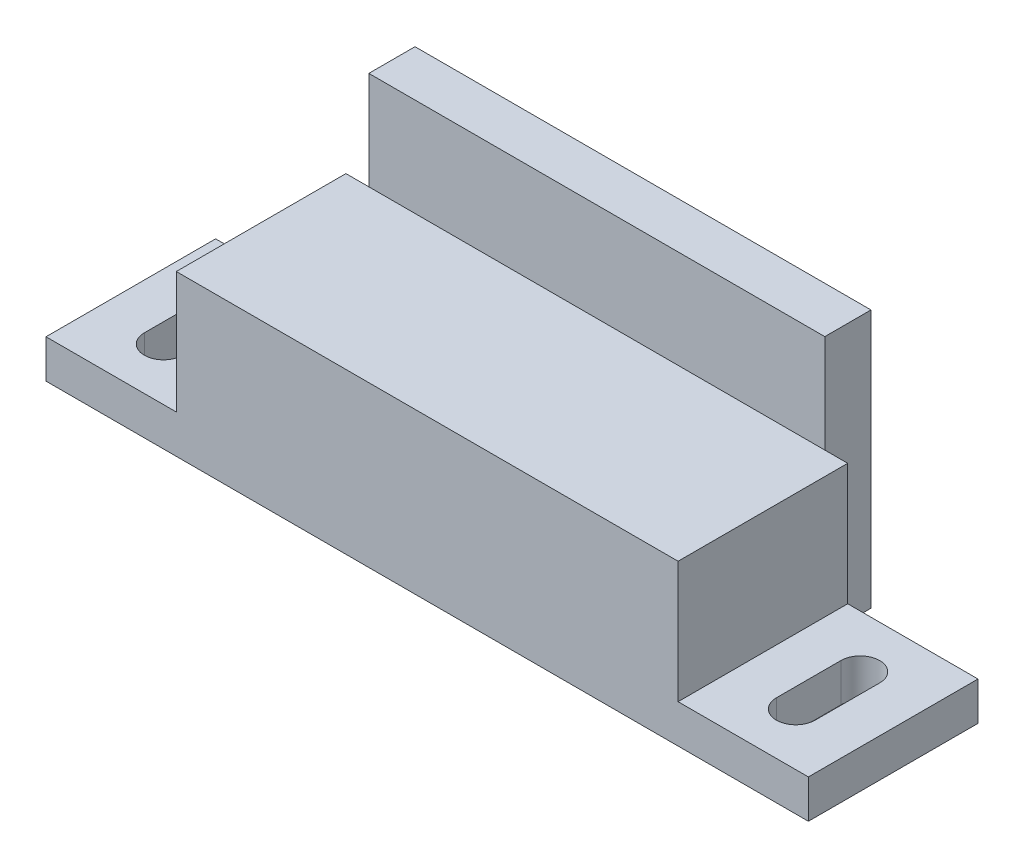
SolidWorks part; units mm, degrees
ref_plane "Front Plane" through (0, 0, 0) normal (0, 0, 1) x (1, 0, 0)
ref_plane "Top Plane" through (0, 0, 0) normal (0, 1, 0) x (1, 0, 0)
ref_plane "Right Plane" through (0, 0, 0) normal (1, 0, 0) x (0, 0, -1)
sketch "Sketch1" plane through (0, 0, 0) normal (0, 0, 1) x (1, 0, 0)
  line L0 (-27.4574, 0) -> (27.4574, 0)
  line L1 (27.4574, 0) -> (27.4574, 2.7686)
  line L2 (27.4574, 2.7686) -> (18.0721, 2.7686)
  line L3 (18.0721, 2.7686) -> (18.0721, 11.5316)
  line L4 (18.0721, 11.5316) -> (-18.0721, 11.5316)
  line L5 (-18.0721, 11.5316) -> (-18.0721, 2.7686)
  line L6 (-18.0721, 2.7686) -> (-27.4574, 2.7686)
  line L7 (-27.4574, 2.7686) -> (-27.4574, 0)
  point P2 (0, 0)
  point P9 (0, 11.5316)
  dimension "D1" = 54.9148
  dimension "D2" = 2.7686
  dimension "D3" = 36.1442
  dimension "D4" = 11.5316
extrude "Boss-Extrude1" add sketch "Sketch1" along normal mid plane 12.2174
sketch "Sketch2" plane through (0, 2.7686, 0) normal (0, 1, 0) x (1, 0, 0)
  line L0 (-27.4574, 0) -> (-18.0721, 0) construction
  line L1 (-27.4574, -6.1087) -> (-27.4574, 6.1087) construction
  line L2 (-18.0721, -6.1087) -> (-18.0721, 6.1087) construction
  line L3 (-22.7647, 6.1087) -> (-22.7647, -6.1087) construction
  line L4 (-18.0721, 6.1087) -> (-27.4574, 6.1087) construction
  line L5 (-18.0721, -6.1087) -> (-27.4574, -6.1087) construction
  line L6 (0, 0) -> (0, -11.0692) construction
  line L7 (-22.7647, 2.3241) -> (-22.7647, -2.3241) construction
  line L8 (-21.3677, 2.3241) -> (-21.3677, -2.3241)
  line L9 (-24.1617, 2.3241) -> (-24.1617, -2.3241)
  line L10 (22.7647, 2.3241) -> (22.7647, -2.3241) construction
  line L11 (21.3677, 2.3241) -> (21.3677, -2.3241)
  line L12 (24.1617, 2.3241) -> (24.1617, -2.3241)
  arc A0 (-21.3677, 2.3241) -> (-24.1617, 2.3241) centre (-22.7647, 2.3241) ccw
  arc A1 (-24.1617, -2.3241) -> (-21.3677, -2.3241) centre (-22.7647, -2.3241) ccw
  arc A2 (21.3677, 2.3241) -> (24.1617, 2.3241) centre (22.7647, 2.3241) cw
  arc A3 (24.1617, -2.3241) -> (21.3677, -2.3241) centre (22.7647, -2.3241) cw
  point P17 (-22.7647, 0)
  point P24 (-22.7647, 0)
  point P27 (22.7647, 0)
  dimension "D1" = 2.794
  dimension "D2" = 4.6482
extrude "Cut-Extrude1" cut sketch "Sketch2" against normal through all
sketch "Sketch3" plane through (0, 0, -6.1087) normal (0, 0, -1) x (-1, 0, 0)
  line L0 (-16.4211, 0) -> (16.4211, 0)
  line L1 (-16.4211, 0) -> (-16.4211, 18.6087)
  line L2 (-16.4211, 18.6087) -> (16.4211, 18.6087)
  line L3 (16.4211, 18.6087) -> (16.4211, 0)
  point P2 (0, 0)
  dimension "D1" = 32.8422
extrude "Boss-Extrude2" add sketch "Sketch3" along normal blind 3.3274
